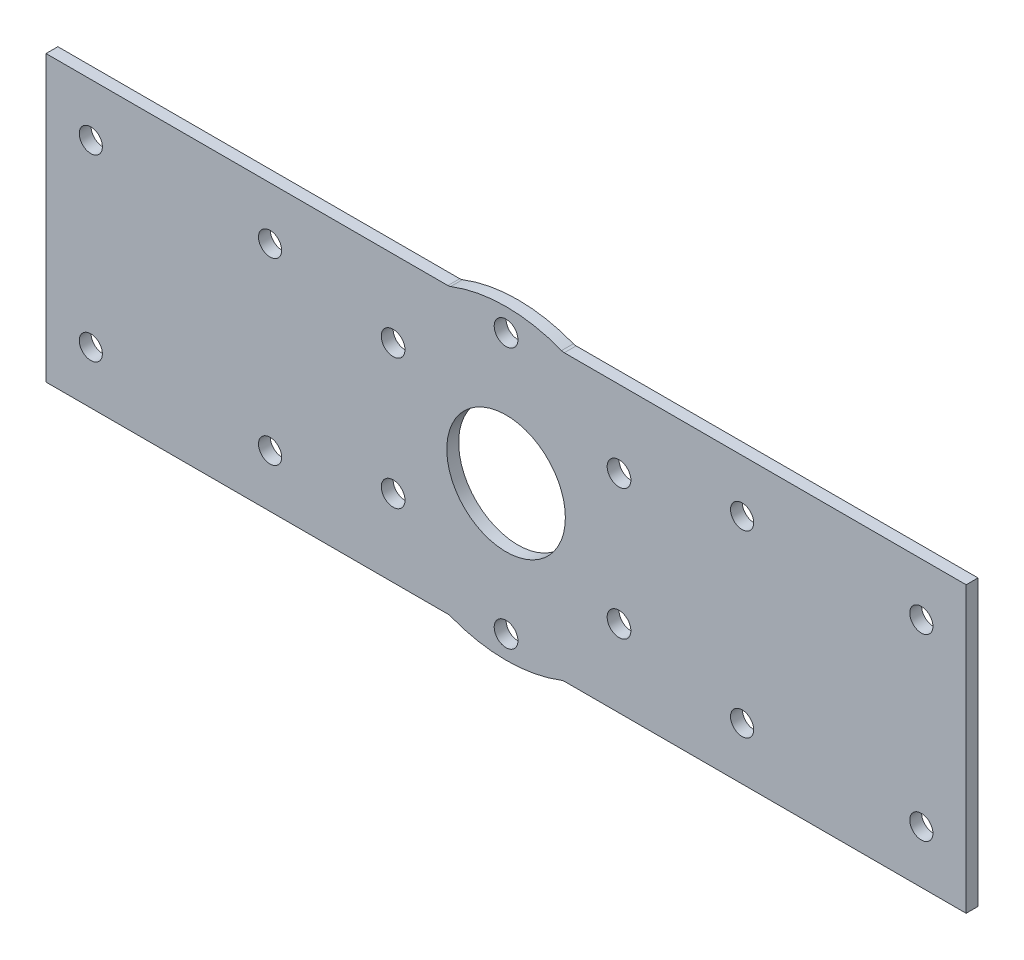
SolidWorks part; units mm, degrees
ref_plane "Front Plane" through (0, 0, 0) normal (0, 0, 1) x (1, 0, 0)
ref_plane "Top Plane" through (0, 0, 0) normal (0, 1, 0) x (1, 0, 0)
ref_plane "Right Plane" through (0, 0, 0) normal (1, 0, 0) x (0, 0, -1)
sketch "Sketch1" plane through (0, 0, 0) normal (0, 0, 1) x (1, 0, 0)
  line L0 (-15.2024, 38.1) -> (-123.2024, 38.1)
  line L1 (-15.2024, -38.1) -> (-123.2024, -38.1)
  line L2 (-123.2024, 38.1) -> (-123.2024, -38.1)
  line L3 (0, 41.021) -> (0, -41.021) construction
  line L4 (-111.2024, 24) -> (-63.2024, 24) construction
  line L5 (-111.2024, 24) -> (-111.2024, -24) construction
  line L6 (-111.2024, -24) -> (-63.2024, -24) construction
  line L7 (-63.2024, 24) -> (-63.2024, -24) construction
  line L8 (-111.2024, 24) -> (-63.2024, -24) construction
  line L9 (-111.2024, -24) -> (-63.2024, 24) construction
  line L10 (15.2024, -38.1) -> (123.2024, -38.1)
  line L11 (123.2024, 38.1) -> (123.2024, -38.1)
  line L12 (15.2024, 38.1) -> (123.2024, 38.1)
  circle A0 centre (0, 0) radius 41.021 construction
  circle A1 centre (-111.2024, 24) radius 3.1
  circle A2 centre (-63.2024, 24) radius 3.1
  circle A3 centre (-63.2024, -24) radius 3.1
  circle A4 centre (-111.2024, -24) radius 3.1
  circle A5 centre (111.2024, -24) radius 3.1
  circle A6 centre (63.2024, -24) radius 3.1
  circle A7 centre (63.2024, 24) radius 3.1
  circle A8 centre (111.2024, 24) radius 3.1
  arc A9 (-15.2024, 38.1) -> (15.2024, 38.1) centre (0, 0) cw
  arc A10 (-15.2024, -38.1) -> (15.2024, -38.1) centre (0, 0) ccw
  circle A11 centre (0, 34.925) radius 3.175
  circle A12 centre (30.2459, 17.4625) radius 3.175
  circle A13 centre (30.2459, -17.4625) radius 3.175
  circle A14 centre (0, -34.925) radius 3.175
  circle A15 centre (-30.2459, -17.4625) radius 3.175
  circle A16 centre (-30.2459, 17.4625) radius 3.175
  circle A17 centre (0, 0) radius 15.875
  point P9 (-123.2024, 0)
  point P10 (-87.2024, 0)
  point P48 (0, 0)
  dimension "D1" = 82.042
  dimension "D7" = 6.2
  dimension "D9" = 6.35
  dimension "D12" = 31.75
  dimension "D2" = 108
  dimension "D3" = 76.2
  dimension "D4" = 12
  dimension "D5" = 48
  dimension "D6" = 48
  dimension "D10" = 34.925
  dimension "D8" = 4
  dimension "D11" = 6
extrude "Boss-Extrude1" add sketch "Sketch1" along normal mid plane 3.175 contours A2 | A6 | A5 | A8 | A3 | A16 | A12 | A13 | A15 | A17 | L0 L2 L1 A10 L10 L11 L12 A9 | A4 | A1 | A7 | A11 | A14
fillet "Fillet1" radius 2 4 edges at (-15.2024, -38.1, 0) (15.2024, -38.1, 0) (-15.2024, 38.1, 0) (15.2024, 38.1, 0)
